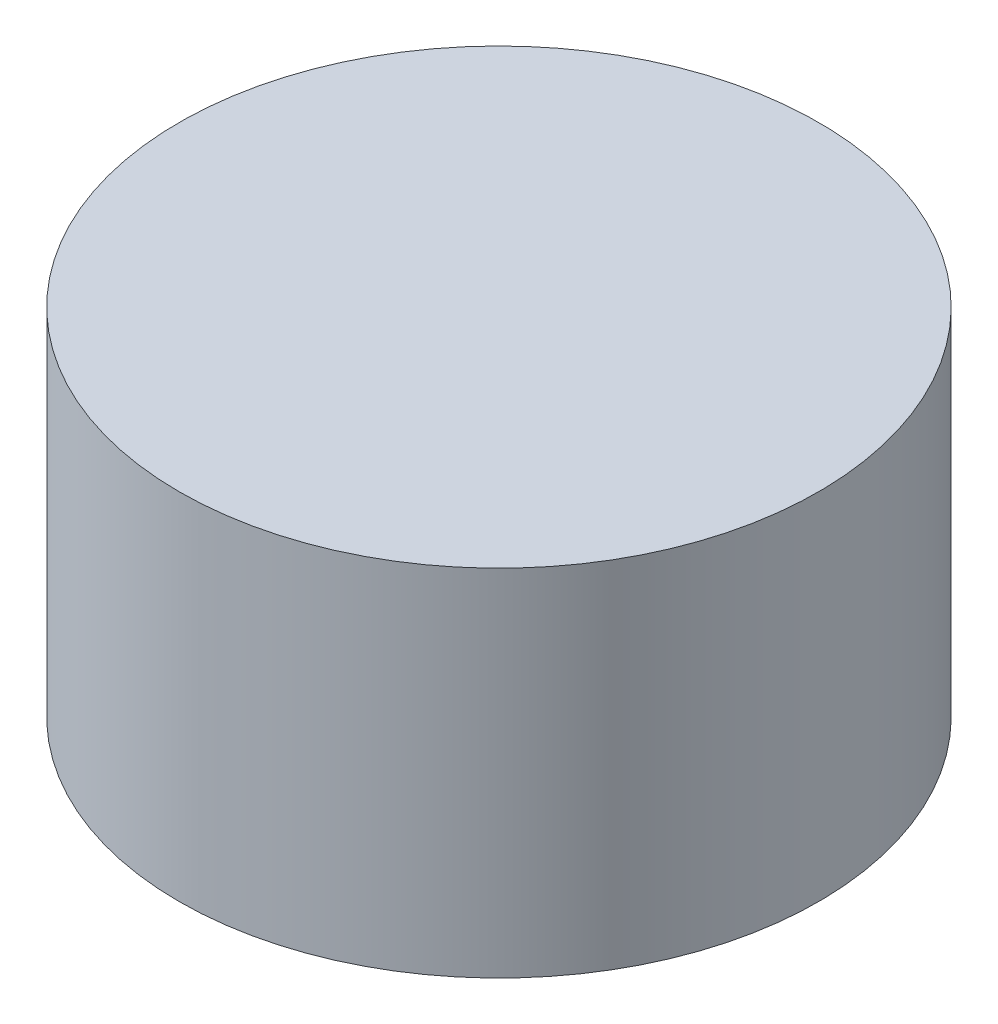
SolidWorks part; units mm, degrees
ref_plane "Front Plane" through (0, 0, 0) normal (0, 0, 1) x (1, 0, 0)
ref_plane "Top Plane" through (0, 0, 0) normal (0, 1, 0) x (1, 0, 0)
ref_plane "Right Plane" through (0, 0, 0) normal (1, 0, 0) x (0, 0, -1)
sketch "Sketch1" plane through (0, 0, 0) normal (0, 1, 0) x (1, 0, 0)
  circle A0 centre (0, 0) radius 3
  dimension "D1" = 6
extrude "Boss-Extrude1" add sketch "Sketch1" along normal blind 3.33
